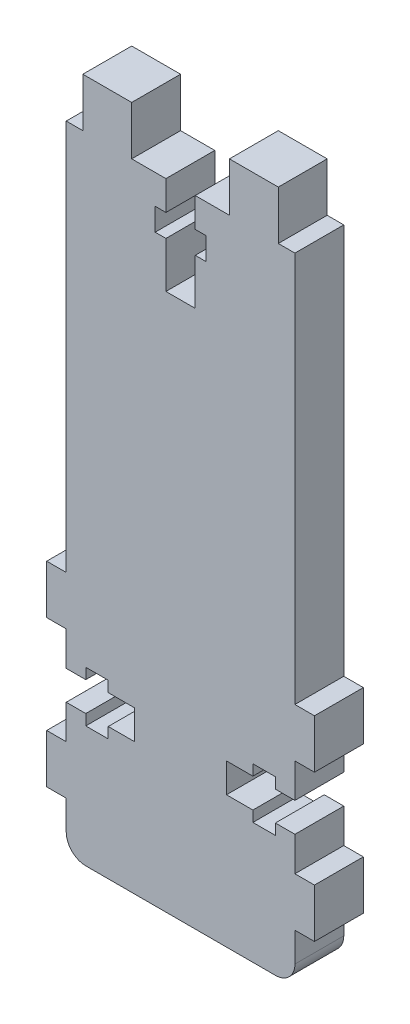
SolidWorks part; units mm, degrees
ref_plane "Plan de face" through (0, 0, 0) normal (0, 0, 1) x (1, 0, 0)
ref_plane "Plan de dessus" through (0, 0, 0) normal (0, 1, 0) x (1, 0, 0)
ref_plane "Plan de droite" through (0, 0, 0) normal (1, 0, 0) x (0, 0, -1)
sketch "Esquisse1" plane through (0, 0, 0) normal (0, 0, 1) x (1, 0, 0)
  line L0 (0, 0) -> (0, 65) construction
  line L1 (0, 65) -> (23.4, 65) construction
  line L2 (23.4, 65) -> (23.4, 0) construction
  line L3 (23.4, 0) -> (0, 0) construction
  line L4 (0, 15) -> (23.4, 15) construction
  line L5 (1.7, 65) -> (0, 65)
  line L6 (0, 65) -> (0, 25)
  line L7 (21.7, 65) -> (23.4, 65)
  line L8 (23.4, 65) -> (23.4, 25)
  line L9 (23.4, 5) -> (23.4, 0)
  line L10 (0, 0) -> (23.4, 0)
  line L12 (0, 0) -> (0, 5)
  line B0 (9.1, 62) -> (9.1, 59.7)
  line B1 (13.2, 59.7) -> (13.2, 55)
  line B2 (10.2, 55) -> (10.2, 59.7)
  line B3 (9.1, 59.7) -> (10.2, 59.7)
  line B4 (11.7, 65) -> (11.7, 53.7792) construction
  line B5 (10.2, 65) -> (6.7, 65)
  line B6 (6.7, 70) -> (1.7, 70)
  line B7 (1.7, 70) -> (1.7, 65)
  line B8 (6.7, 70) -> (6.7, 65)
  line B9 (13.2, 65) -> (16.7, 65)
  line B10 (16.7, 65) -> (16.7, 70)
  line B11 (16.7, 70) -> (21.7, 70)
  line B12 (21.7, 70) -> (21.7, 65)
  line B13 (10.2, 65) -> (13.2, 65) construction
  line B14 (13.2, 65) -> (13.2, 62)
  line B15 (13.2, 59.7) -> (14.3, 59.7)
  line B16 (14.3, 62) -> (13.2, 62)
  line B17 (13.2, 55) -> (10.2, 55)
  line B18 (10.2, 62) -> (9.1, 62)
  line B19 (14.3, 59.7) -> (14.3, 62)
  line B20 (10.2, 62) -> (10.2, 65)
  line B21 (11.7, 55) -> (11.7, 65) construction
  line B22 (23.3419, 15) -> (9.4468, 15) construction
  line B23 (23.4, 13.5) -> (23.4, 10)
  line B24 (25.4, 10) -> (25.4, 5)
  line B25 (25.4, 5) -> (23.4, 5)
  line B26 (25.4, 10) -> (23.4, 10)
  line B27 (23.4, 16.2928) -> (23.4, 20)
  line B28 (23.4, 20) -> (25.4, 20)
  line B29 (25.4, 20) -> (25.4, 25)
  line B30 (25.4, 25) -> (23.4, 25)
  line B31 (23.4, 13.5) -> (23.4, 16.5) construction
  line B32 (23.4, 16.5) -> (21.4, 16.5)
  line B33 (19.1, 16.5) -> (19.1, 17.6)
  line B34 (21.4, 12.4) -> (19.1, 12.4)
  line B35 (21.4, 17.6) -> (21.4, 16.5)
  line B36 (19.1, 16.5) -> (16.4, 16.5)
  line B37 (16.4, 16.5) -> (16.4, 13.5)
  line B38 (16.4, 13.5) -> (19.1, 13.5)
  line B39 (21.4, 13.5) -> (21.4, 12.4)
  line B40 (19.1, 17.6) -> (21.4, 17.6)
  line B41 (19.1, 12.4) -> (19.1, 13.5)
  line B42 (21.4, 13.5) -> (23.4, 13.5)
  line B43 (16.4, 15) -> (23.4, 15) construction
  line B44 (0.0581, 15) -> (13.9532, 15) construction
  line B45 (0, 13.5) -> (0, 10)
  line B46 (-2, 10) -> (-2, 5)
  line B47 (-2, 5) -> (0, 5)
  line B48 (-2, 10) -> (0, 10)
  line B49 (0, 16.2928) -> (0, 20)
  line B50 (0, 20) -> (-2, 20)
  line B51 (-2, 20) -> (-2, 25)
  line B52 (-2, 25) -> (0, 25)
  line B53 (0, 13.5) -> (0, 16.5) construction
  line B54 (0, 16.5) -> (2, 16.5)
  line B55 (4.3, 16.5) -> (4.3, 17.6)
  line B56 (2, 12.4) -> (4.3, 12.4)
  line B57 (2, 17.6) -> (2, 16.5)
  line B58 (4.3, 16.5) -> (7, 16.5)
  line B59 (7, 16.5) -> (7, 13.5)
  line B60 (7, 13.5) -> (4.3, 13.5)
  line B61 (2, 13.5) -> (2, 12.4)
  line B62 (4.3, 17.6) -> (2, 17.6)
  line B63 (4.3, 12.4) -> (4.3, 13.5)
  line B64 (2, 13.5) -> (0, 13.5)
  line B65 (7, 15) -> (0, 15) construction
  dimension "D1" = 23.4
  dimension "D2" = 15
  dimension "D3" = 50
sketch_block_instance "Insert M3 plots ep 5mm-13"
sketch_block "Insert M3 plots ep 5mm" parameters "D1"=10, "D2"=5, "D3"=5
sketch_block_instance "Decoupe Insert M3-4"
sketch_block "Decoupe Insert M3" parameters "D1"=5.2, "D2"=3, "D3"=2.3, "D4"=3, "D5"=10
sketch_block_instance "Bloc1-1"
sketch_block "Bloc1" parameters "D1"=10, "D2"=5, "D3"=2
sketch_block_instance "Bloc3-3"
sketch_block "Bloc3" parameters "D1"=5.2, "D2"=3, "D3"=2.3, "D4"=2, "D5"=7
sketch_block_instance "Bloc1-3"
extrude "Boss.-Extru.1" add sketch "Esquisse1" along normal blind 5
fillet "Fillet1" radius 2 2 edges at (0, 0, 2.5) (23.4, 0, 2.5)
